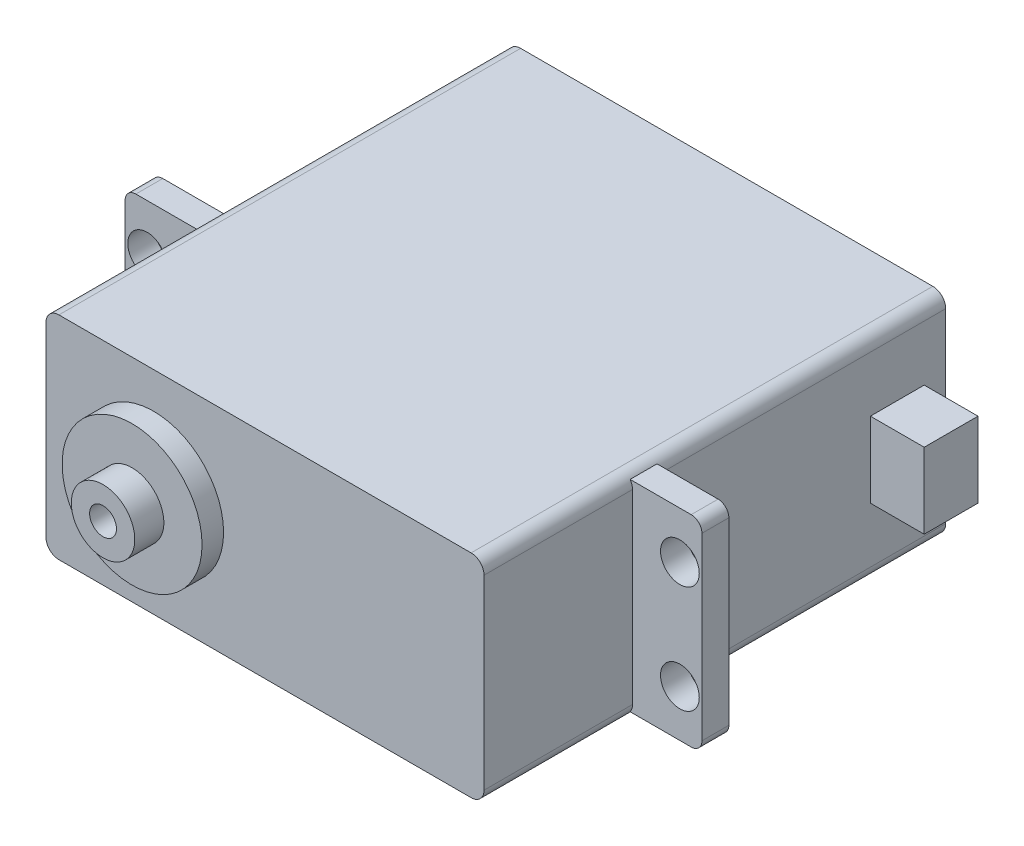
SolidWorks part; units mm, degrees
ref_plane "Front Plane" through (0, 0, 0) normal (0, 0, 1) x (1, 0, 0)
ref_plane "Top Plane" through (0, 0, 0) normal (0, 1, 0) x (1, 0, 0)
ref_plane "Right Plane" through (0, 0, 0) normal (1, 0, 0) x (0, 0, -1)
sketch "Sketch1" plane through (0, 0, 0) normal (0, 0, 1) x (1, 0, 0)
  line L0 (-8.8, -9.85) -> (29.5, -9.85)
  line L1 (30.7, -8.65) -> (30.7, 8.65)
  line L2 (29.5, 9.85) -> (-8.8, 9.85)
  line L3 (-10, 8.65) -> (-10, -8.65)
  arc A0 (-10, -8.65) -> (-8.8, -9.85) centre (-8.8, -8.65) ccw
  arc A1 (29.5, -9.85) -> (30.7, -8.65) centre (29.5, -8.65) ccw
  arc A2 (30.7, 8.65) -> (29.5, 9.85) centre (29.5, 8.65) ccw
  arc A3 (-8.8, 9.85) -> (-10, 8.65) centre (-8.8, 8.65) ccw
extrude "Case" add sketch "Sketch1" along normal blind 42.9 from offset 42.9
sketch "Sketch2" plane through (0, 0, 0) normal (0, 0, 1) x (1, 0, 0)
  line L0 (-15.45, -9.35) -> (36.15, -9.35)
  line L1 (37.15, -8.35) -> (37.15, 8.35)
  line L2 (36.15, 9.35) -> (-15.45, 9.35)
  line L3 (-16.45, 8.35) -> (-16.45, -8.35)
  arc A0 (-16.45, -8.35) -> (-15.45, -9.35) centre (-15.45, -8.35) ccw
  arc A1 (36.15, -9.35) -> (37.15, -8.35) centre (36.15, -8.35) ccw
  arc A2 (37.15, 8.35) -> (36.15, 9.35) centre (36.15, 8.35) ccw
  arc A3 (-15.45, 9.35) -> (-16.45, 8.35) centre (-15.45, 8.35) ccw
  circle A4 centre (-14.4, -5) radius 1.8
  circle A5 centre (-14.4, 5) radius 1.8
  circle A6 centre (35.1, -5) radius 1.8
  circle A7 centre (35.1, 5) radius 1.8
extrude "Tabs" add sketch "Sketch2" along normal blind 2.5 from offset 16.3
sketch "Sketch3" plane through (0, 0, 0) normal (0, 0, 1) x (1, 0, 0)
  circle A0 centre (0, 0) radius 6.5
extrude "Boss" add sketch "Sketch3" along normal blind 2
sketch "Sketch4" plane through (0, 0, 0) normal (0, 0, 1) x (1, 0, 0)
  circle A0 centre (0, 0) radius 2.95
extrude "Spline" add sketch "Sketch4" along normal blind 2.7 from offset 2
sketch "Sketch5" plane through (0, 0, 0) normal (0, 0, 1) x (1, 0, 0)
  circle A0 centre (0, 0) radius 1.25
extrude "M3 tap" cut sketch "Sketch5" along normal blind 4.1 from offset 0.7
sketch "Sketch6" plane through (0, 0, 0) normal (1, 0, 0) x (0, 0, -1)
  line L0 (35.9, -3.5) -> (40.9, -3.5)
  line L1 (40.9, -3.5) -> (40.9, 3.5)
  line L2 (40.9, 3.5) -> (35.9, 3.5)
  line L3 (35.9, 3.5) -> (35.9, -3.5)
extrude "Lead" add sketch "Sketch6" along normal blind 5.2 from offset 30.5
